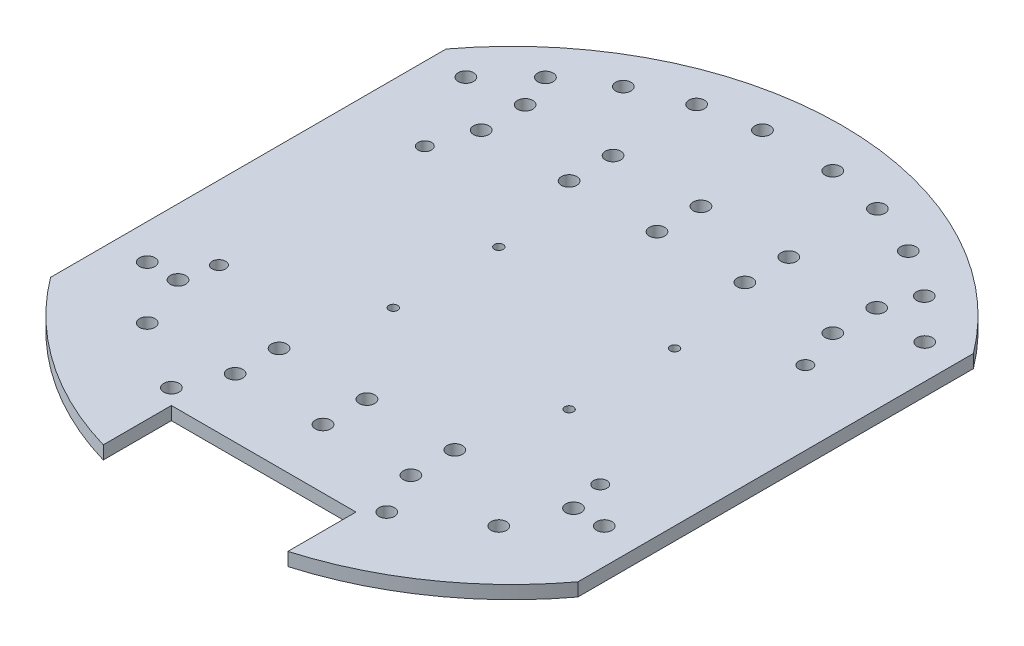
SolidWorks part; units mm, degrees
ref_plane "Front Plane" through (0, 0, 0) normal (0, 0, 1) x (1, 0, 0)
ref_plane "Top Plane" through (0, 0, 0) normal (0, 1, 0) x (1, 0, 0)
ref_plane "Right Plane" through (0, 0, 0) normal (1, 0, 0) x (0, 0, -1)
sketch "Sketch1" plane through (0, 0, 0) normal (0, 1, 0) x (1, 0, 0)
  circle A0 centre (0, 0) radius 75
  dimension "D1" = 150
extrude "Boss-Extrude1" add sketch "Sketch1" along normal blind 3
sketch "Sketch2" plane through (0, 3, 0) normal (0, 1, 0) x (1, 0, 0)
  line L0 (-79.1927, 0) -> (-42.5806, 0) construction
  line L1 (-79.1927, 60) -> (-60, 60)
  line L2 (-79.1927, 60) -> (-79.1927, -60)
  line L3 (-79.1927, -60) -> (-60, -60)
  line L4 (-60, 60) -> (-60, -60)
  dimension "D1" = 60
  dimension "D2" = 120
  dimension "D3" = 60
extrude "Cut-Extrude1" cut sketch "Sketch2" against normal blind 4
mirror "Mirror1" about plane through (0, 0, 0) normal (1, 0, 0) of "Cut-Extrude1"
hole_wizard "Ø3.5 (3.5) Diameter Hole1" positions "Sketch9" profile "Sketch10" hole size "Ø3.5" standard "ISO"
sketch "Sketch9" plane through (0, 0, 0) normal (0, -1, 0) x (-1, 0, 0)
  point P7 (40, -43)
  point P10 (-40, -43)
  point P16 (-40, 43)
  point P19 (40, 43)
  dimension "D1" = 40
  dimension "D2" = 80
  dimension "D3" = 43
  dimension "D4" = 86
sketch "Sketch10" plane through (-40, 0, 43) normal (1, 0, 0) x (0, 0, -1)
  line L0 (0, 0) -> (0, 5.0515)
  line L1 (0, 5.0515) -> (1.75, 4)
  line L2 (1.75, 4) -> (1.75, 0)
  line L5 (1.75, 0) -> (0, 0)
  line L10 (0, 5.0515) -> (-1.75, 4) construction
  line L11 (0, -6.35) -> (0, 107.95) construction
  dimension "Hole Dia." = 3.5
  dimension "Hole Depth" = 4
  dimension "Drill Angle" = 118
hole_wizard "Ø2.0 (2) Diameter Hole1" positions "Sketch11" profile "Sketch12" hole size "Ø2.0" standard "ISO"
sketch "Sketch11" plane through (0, 3, 0) normal (0, 1, 0) x (1, 0, 0)
  point P0 (25, -12)
  point P3 (25, 12)
  point P6 (-15, 12)
  point P9 (-15, -12)
sketch "Sketch12" plane through (25, 3, 12) normal (1, 0, 0) x (0, 0, 1)
  line L0 (0, 0) -> (0, 5.6009)
  line L1 (0, 5.6009) -> (1, 5)
  line L2 (1, 5) -> (1, 0)
  line L5 (1, 0) -> (0, 0)
  line L10 (0, 5.6009) -> (-1, 5) construction
  line L11 (0, -6.35) -> (0, 107.95) construction
  dimension "Hole Dia." = 2
  dimension "Hole Depth" = 5
  dimension "Drill Angle" = 118
sketch "Sketch15" plane through (0, 3, 0) normal (0, 1, 0) x (1, 0, 0)
  line L0 (-16, -61.5) -> (-16, -63.1) construction
  line L1 (-16, -63.1) -> (16, -63.1) construction
  line L2 (16, -63.1) -> (16, -61.5) construction
  line L3 (16, -61.5) -> (-16, -61.5) construction
  line L4 (21, -72) -> (21, -56.5)
  line L5 (21, -56.5) -> (-21, -56.5)
  line L6 (-21, -56.5) -> (-21, -72)
  line L7 (-21, -56.5) -> (-21, -63.1) construction
  line L8 (21, -63.1) -> (21, -56.5) construction
  line L11 (60, -45) -> (60, 45)
  line L12 (-60, 45) -> (-60, -45)
  line L13 (60, -45) -> (60, 45)
  line L14 (-60, 45) -> (-60, -45)
  arc A0 (-60, -45) -> (60, -45) centre (0, 0) ccw construction
  arc A3 (-60, -45) -> (60, -45) centre (0, 0) ccw
  arc A4 (60, 45) -> (-60, 45) centre (0, 0) ccw
  arc A5 (-60, -45) -> (60, -45) centre (0, 0) ccw
  arc A6 (60, 45) -> (-60, 45) centre (0, 0) ccw
  arc M9 (-60, -45) -> (60, -45) centre (0, 0) ccw
  dimension "D1" = 5
  dimension "D2" = 0
extrude "Cut-Extrude2" cut sketch "Sketch15" against normal blind 10 contours L5 L6 L4 M9
sketch "Sketch18" plane through (0, 3, 0) normal (0, 1, 0) x (1, 0, 0)
  line L0 (60, -45) -> (60, 45) construction
  circle A0 centre (-43.2576, 23.425) radius 1.525
  circle A1 centre (-43.2576, -23.425) radius 1.525
  circle A2 centre (43.1701, 23.5858) radius 1.525
  circle A3 centre (43.3445, -23.2639) radius 1.525
  dimension "D1" = 3.05
  dimension "D2" = 16.6555
  dimension "D3" = 16.8299
  dimension "D4" = 103.2576
  dimension "D5" = 21.4142
  dimension "D6" = 21.575
  dimension "D7" = 68.2639
  dimension "D8" = 68.425
extrude "Cut-Extrude3" cut sketch "Sketch18" against normal blind 10
sketch "Sketch19" plane through (0, 3, 0) normal (0, 1, 0) x (1, 0, 0)
  line L0 (60, -45) -> (60, 45) construction
  circle A0 centre (-8, 65) radius 1.75
  circle A1 centre (8, 65) radius 1.75
  circle A2 centre (-20.5656, 62.5805) radius 1.75
  circle A3 centre (-32.4177, 57.7561) radius 1.75
  circle A4 centre (-43.1009, 50.7121) radius 1.75
  circle A5 centre (-52.2046, 41.7193) radius 1.75
  circle A6 centre (20.5656, 62.5805) radius 1.75
  circle A7 centre (32.4177, 57.7561) radius 1.75
  circle A8 centre (43.1009, 50.7121) radius 1.75
  circle A9 centre (52.2046, 41.7193) radius 1.75
  point P4 (0, 0)
  point P17 (-2, 0)
  point P25 (2, 0)
  dimension "D1" = 3.5
  dimension "D2" = 3.5
  dimension "D3" = 65
  dimension "D4" = 65
  dimension "D5" = 8
  dimension "D9" = 12.5656
  dimension "D10" = 62.5805
  dimension "D11" = 11.8521
  dimension "D12" = 12.5656
  dimension "D13" = 62.5805
  dimension "D14" = 11.8521
  dimension "D6" = 8
  dimension "D7" = 5
  dimension "D8" = 5
extrude "Cut-Extrude4" cut sketch "Sketch19" against normal blind 10 contours A3 | A2 | A0 | A1 | A6 | A7 | A8 | A5 | A4 | A9
sketch "Sketch21" plane through (0, 3, 0) normal (0, 1, 0) x (1, 0, 0)
  line L0 (21, -72) -> (21, -56.5) construction
  line L5 (21, -56.5) -> (21, -72)
  line L6 (60, -45) -> (60, 45)
  line L7 (-60, 45) -> (-60, -45)
  line L8 (-21, -72) -> (-21, -56.5)
  line L9 (-21, -56.5) -> (21, -56.5)
  line L10 (21, -56.5) -> (21, -72)
  line L11 (60, -45) -> (60, 45)
  line L12 (-60, 45) -> (-60, -45)
  line L13 (-21, -72) -> (-21, -56.5)
  line L14 (-21, -56.5) -> (21, -56.5)
  circle A0 centre (40, -43) radius 1.75 construction
  circle A1 centre (-40, -43) radius 1.75 construction
  circle A2 centre (40, 43) radius 1.75 construction
  circle A3 centre (-40, 43) radius 1.75 construction
  circle A4 centre (40, -43) radius 1.75
  circle A5 centre (-40, -43) radius 1.75
  circle A6 centre (40, 43) radius 1.75
  circle A7 centre (-40, 43) radius 1.75
  circle A8 centre (-20, 43) radius 1.75
  circle A9 centre (0, 43) radius 1.75
  circle A10 centre (20, 43) radius 1.75
  circle A11 centre (-20, -43) radius 1.75
  circle A12 centre (0, -43) radius 1.75
  circle A13 centre (20, -43) radius 1.75
  circle A14 centre (-24.5, -53) radius 1.75
  circle A15 centre (24.5, -53) radius 1.75
  circle A16 centre (-52, -31) radius 1.75
  circle A17 centre (-45, -31) radius 1.75
  circle A18 centre (45, -31) radius 1.75
  arc A19 (21, -72) -> (60, -45) centre (0, 0) ccw
  arc A20 (60, 45) -> (-60, 45) centre (0, 0) ccw
  arc A21 (-60, -45) -> (-21, -72) centre (0, 0) ccw
  arc A22 (21, -72) -> (60, -45) centre (0, 0) ccw
  arc A23 (60, 45) -> (-60, 45) centre (0, 0) ccw
  arc A24 (-60, -45) -> (-21, -72) centre (0, 0) ccw
  circle A25 centre (52, -31) radius 1.75
  circle A26 centre (-40, 33) radius 1.75
  circle A27 centre (-20, 33) radius 1.75
  circle A28 centre (0, 33) radius 1.75
  circle A29 centre (20, 33) radius 1.75
  circle A30 centre (40, 33) radius 1.75
  circle A31 centre (-20, -33) radius 1.75
  circle A32 centre (0, -33) radius 1.75
  circle A33 centre (20, -33) radius 1.75
  dimension "D3" = 3.5
  dimension "D4" = 3.5
  dimension "D6" = 3.5
  dimension "D7" = 3.5
  dimension "D8" = 3.5
  dimension "D9" = 3.5
  dimension "D10" = 20
  dimension "D11" = 20
  dimension "D12" = 3.5
  dimension "D13" = 3.5
  dimension "D14" = 3.5
  dimension "D15" = 3.5
  dimension "D16" = 5
  dimension "D17" = 12
  dimension "D18" = 12
  dimension "D19" = 7
  dimension "D20" = 7
  dimension "D21" = 5
  dimension "D22" = 12
  dimension "D23" = 12
  dimension "D26" = 10
  dimension "D27" = 10
  dimension "D5" = 0
  dimension "D1" = 4
  dimension "D2" = 4
  dimension "D24" = 2
  dimension "D25" = 2
extrude "Cut-Extrude5" cut sketch "Sketch21" against normal up to next contours A16 | A14 | A11 | A12 | A13 | A15 | A18 | A25 | A10 | A9 | A17 | A8 | A31 | A32 | A33 | A26 | A27 | A28 | A29 | A30
equation "\"D3@Sketch9\"=86/2"
